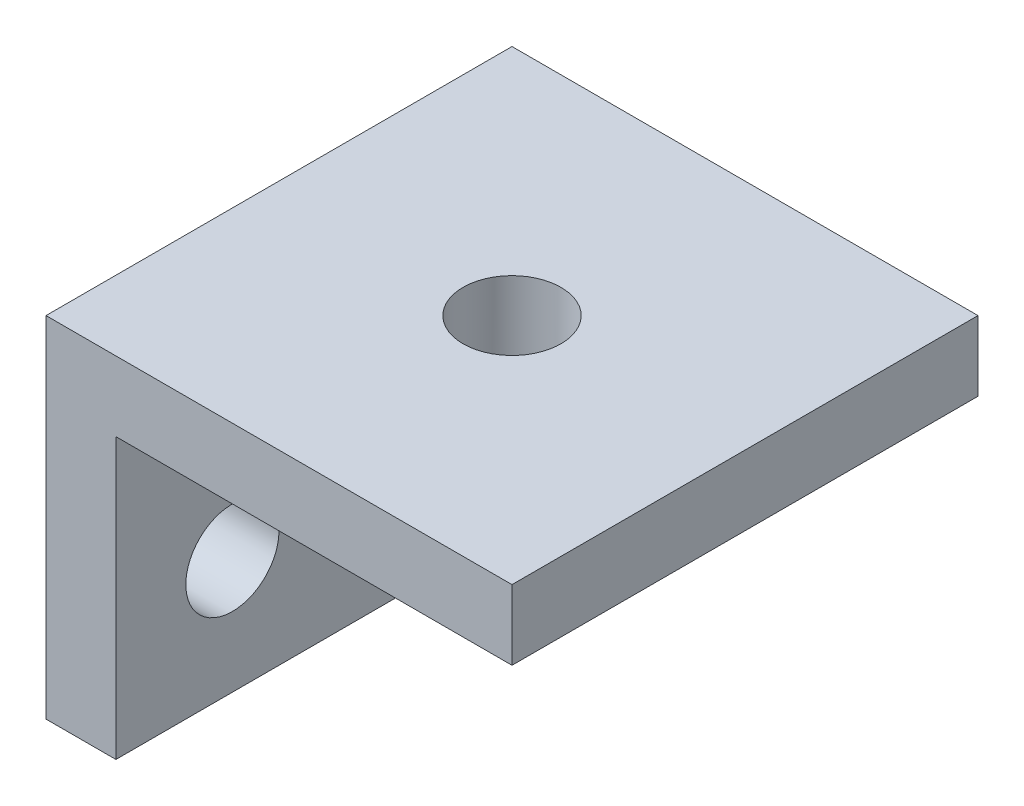
SolidWorks part; units mm, degrees
ref_plane "前视基准面" through (0, 0, 0) normal (0, 0, 1) x (1, 0, 0)
ref_plane "上视基准面" through (0, 0, 0) normal (0, 1, 0) x (1, 0, 0)
ref_plane "右视基准面" through (0, 0, 0) normal (1, 0, 0) x (0, 0, -1)
ref_plane "基准面4" through (0, -25, 0) normal (0, -1, 0) x (1, 0, 0)
sketch "草图1" plane through (0, -25, 0) normal (0, -1, 0) x (1, 0, 0)
  line L0 (-36, 0) -> (-16, 0)
  line L1 (-16, 0) -> (-16, 20)
  line L2 (-16, 20) -> (-36, 20)
  line L3 (-36, 20) -> (-36, 0)
extrude "凸台-拉伸1" add sketch "草图1" against normal blind 15
sketch "草图2" plane through (0, 0, 0) normal (0, 0, -1) x (-1, 0, 0)
  line L0 (16, -25) -> (33, -25)
  line L1 (33, -25) -> (33, -13)
  line L2 (33, -13) -> (16, -13)
  line L3 (16, -13) -> (16, -25)
extrude "切除-拉伸1" cut sketch "草图2" against normal through all
hole_wizard "Ø4.2 (4.2) 直径孔1" positions "草图4" profile "草图3" hole size "Ø4.2" standard "ANSI Metric"
sketch "草图4" plane through (0, -10, 0) normal (0, 1, 0) x (1, 0, 0)
  point P0 (-26, -10)
sketch "草图3" plane through (-26, -10, 10) normal (1, 0, 0) x (0, 0, 1)
  line L0 (0, 0) -> (0, 15)
  line L1 (0, 15) -> (2.1, 15)
  line L2 (2.1, 15) -> (2.1, 0)
  line L5 (2.1, 0) -> (0, 0)
  line L11 (0, -6.35) -> (0, 107.95) construction
  dimension "通孔孔直径" = 4.2
  dimension "通孔孔深度" = 15
hole_wizard "Ø4.0 (4) 直径孔1" positions "草图6" profile "草图5" hole size "Ø4.0" standard "ANSI Metric"
sketch "草图6" plane through (-33, 0, 0) normal (1, 0, 0) x (0, 0, -1)
  point P0 (-15, -20)
  point P1 (-5, -20)
sketch "草图5" plane through (-33, -20, 15) normal (0, 1, 0) x (0, 0, -1)
  line L0 (0, 0) -> (0, 3)
  line L1 (0, 3) -> (2, 3)
  line L2 (2, 3) -> (2, 0)
  line L5 (2, 0) -> (0, 0)
  line L11 (0, -6.35) -> (0, 107.95) construction
  dimension "通孔孔直径" = 4
  dimension "通孔孔深度" = 3
